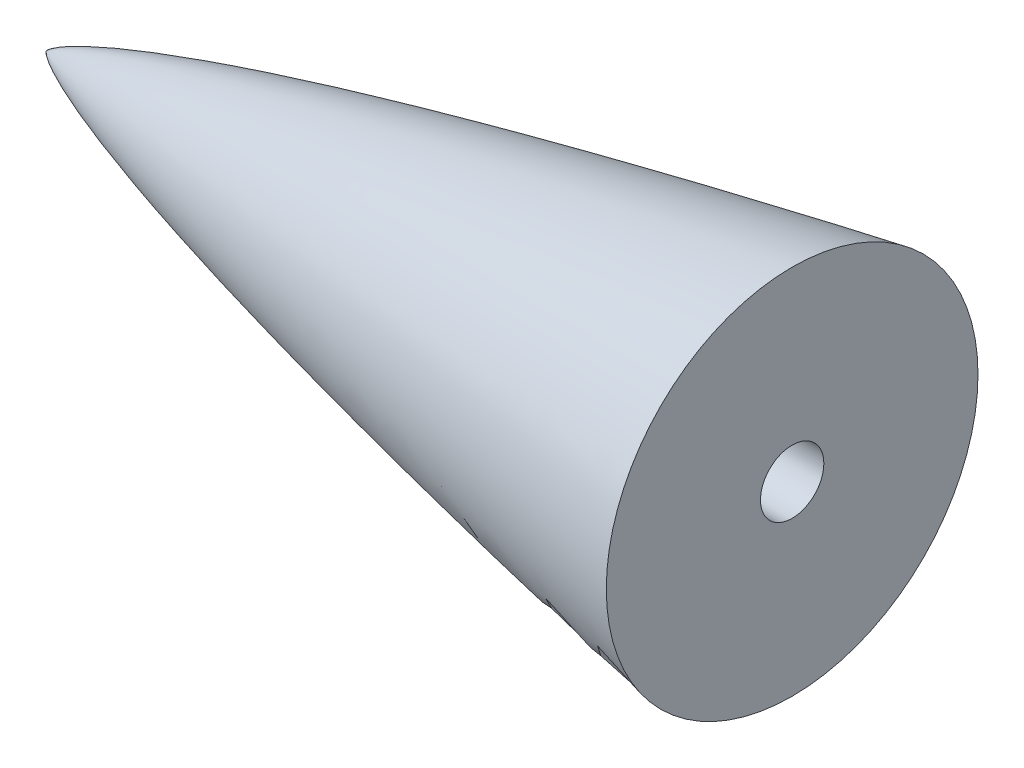
SolidWorks part; units mm, degrees
material "6061 Alloy"
ref_plane "Front Plane" through (0, 0, 0) normal (0, 0, 1) x (1, 0, 0)
ref_plane "Top Plane" through (0, 0, 0) normal (0, 1, 0) x (1, 0, 0)
ref_plane "Right Plane" through (0, 0, 0) normal (1, 0, 0) x (0, 0, -1)
sketch "Sketch1" plane through (0, 0, 0) normal (0, 0, 1) x (1, 0, 0)
  line L0 (-5.1863, 0) -> (54.4485, 0) construction
  line L1 (522, 64) -> (522, 0)
  line L2 (522, 0) -> (0, 0)
  spline S0 degree 4 poles (0, 0) (0.0018, 0.0068) (0.0068, 0.0199) (0.0215, 0.0442) (0.0467, 0.078) (0.0793, 0.115) (0.1266, 0.1631) (0.1847, 0.2162) (0.2537, 0.2739) (0.3336, 0.3359) (0.4604, 0.4286) (0.6604, 0.5626) (0.983, 0.7589) (1.5346, 1.0602) (2.4651, 1.5146) (4.1232, 2.2301) (7.1931, 3.3881) (12.88, 5.2403) (22.6082, 7.9618) (39.4821, 12.0346) (62.844, 16.8724) (91.3889, 22.0777) (123.5069, 27.3148) (155.6948, 32.0989) (187.9363, 36.5067) (220.2205, 40.5877) (252.5411, 44.3705) (284.893, 47.8734) (313.2258, 50.7004) (337.5272, 52.9543) (357.7887, 54.7172) (374.0038, 56.0569) (390.2249, 57.3236) (406.4516, 58.5145) (422.6841, 59.6255) (436.8924, 60.523) (449.0744, 61.2343) (459.2285, 61.7853) (467.3531, 62.1993) (474.4634, 62.5365) (480.5589, 62.8061) (485.639, 63.0167) (489.7035, 63.1763) (496.0257, 63.4099) (502.1511, 63.6094) (508.0796, 63.7737) (513.8111, 63.8964) (516.677, 63.9464) (519.1337, 63.9803) (520.7716, 63.9943) (521.5905, 64) (522, 64) knots 0 0 0 0 0 0.000053 0.000107 0.000213 0.00032 0.000427 0.000619 0.00081 0.001002 0.001194 0.00181 0.002636 0.003865 0.005961 0.009663 0.016332 0.028748 0.05132 0.086279 0.147994 0.20971 0.271425 0.333141 0.394856 0.456572 0.518288 0.580003 0.641719 0.672577 0.703434 0.734292 0.76515 0.796008 0.826866 0.857723 0.873152 0.888581 0.90401 0.919439 0.927153 0.934868 0.942582 0.950297 0.975148 0.981361 0.987574 0.993787 0.996894 1 1 1 1 1 construction
  spline S1 degree 4 poles (0, 0) (0.0018, 0.0068) (0.0068, 0.0199) (0.0215, 0.0442) (0.0467, 0.078) (0.0793, 0.115) (0.1266, 0.1631) (0.1847, 0.2162) (0.2537, 0.2739) (0.3336, 0.3359) (0.4604, 0.4286) (0.6604, 0.5626) (0.983, 0.7589) (1.5346, 1.0602) (2.4651, 1.5146) (4.1232, 2.2301) (7.1931, 3.3881) (12.88, 5.2403) (22.6082, 7.9618) (39.4821, 12.0346) (62.844, 16.8724) (91.3889, 22.0777) (123.5069, 27.3148) (155.6948, 32.0989) (187.9363, 36.5067) (220.2205, 40.5877) (252.5411, 44.3705) (284.893, 47.8734) (313.2258, 50.7004) (337.5272, 52.9543) (357.7887, 54.7172) (374.0038, 56.0569) (390.2249, 57.3236) (406.4516, 58.5145) (422.6841, 59.6255) (436.8924, 60.523) (449.0744, 61.2343) (459.2285, 61.7853) (467.3531, 62.1993) (474.4634, 62.5365) (480.5589, 62.8061) (485.639, 63.0167) (489.7035, 63.1763) (496.0257, 63.4099) (502.1511, 63.6094) (508.0796, 63.7737) (513.8111, 63.8964) (516.677, 63.9464) (519.1337, 63.9803) (520.7716, 63.9943) (521.5905, 64) (522, 64) knots 0 0 0 0 0 0.000053 0.000107 0.000213 0.00032 0.000427 0.000619 0.00081 0.001002 0.001194 0.00181 0.002636 0.003865 0.005961 0.009663 0.016332 0.028748 0.05132 0.086279 0.147994 0.20971 0.271425 0.333141 0.394856 0.456572 0.518288 0.580003 0.641719 0.672577 0.703434 0.734292 0.76515 0.796008 0.826866 0.857723 0.873152 0.888581 0.90401 0.919439 0.927153 0.934868 0.942582 0.950297 0.975148 0.981361 0.987574 0.993787 0.996894 1 1 1 1 1
revolve "nosecone" add sketch "Sketch1" angle 360 about L0
ref_plane "kutt" through (80, 0, 0) normal (1, 0, 0) x (0, 0, -1)
other "SurfaceCut1"
sketch "Sketch2" plane through (80, 0, 0) normal (1, 0, 0) x (0, 0, -1)
  circle A0 centre (0, 0) radius 3.4
  dimension "D1" = 6.8
extrude "Cut-Extrude1" cut sketch "Sketch2" against normal blind 40
cosmetic thread "Cosmetic Thread1" parameters "D2"=8
